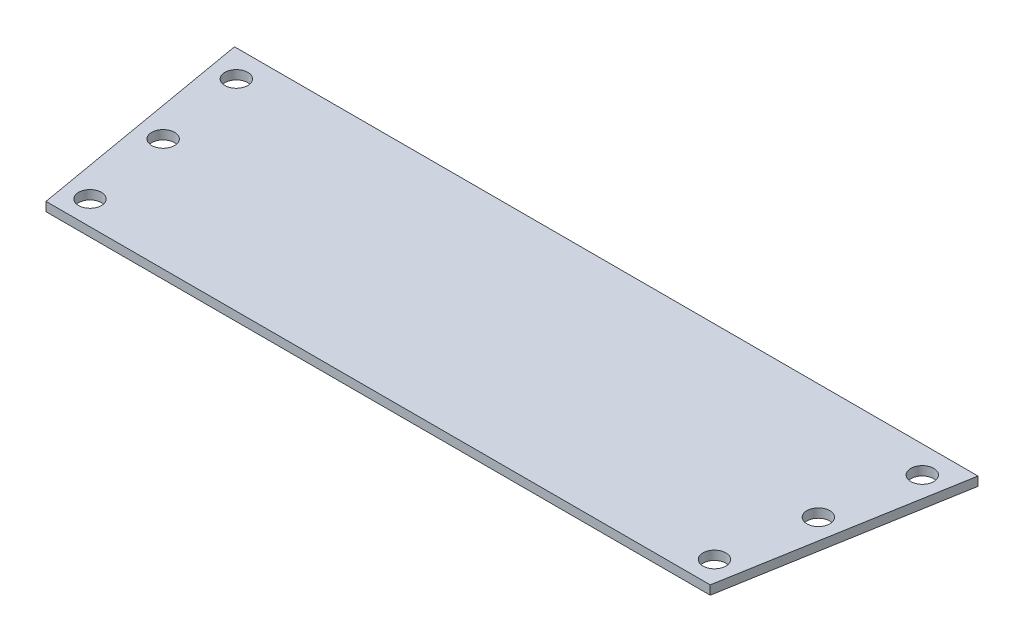
SolidWorks part; units mm, degrees
ref_plane "前视基准面" through (0, 0, 0) normal (0, 0, 1) x (1, 0, 0)
ref_plane "上视基准面" through (0, 0, 0) normal (0, 1, 0) x (1, 0, 0)
ref_plane "右视基准面" through (0, 0, 0) normal (1, 0, 0) x (0, 0, -1)
sketch "草图1" plane through (0, 0, 0) normal (0, 1, 0) x (1, 0, 0)
  line L14 (-100, 30) -> (100, 30)
  line L15 (-100, 30) -> (-100, -30)
  line L16 (-100, -30) -> (100, -30)
  line L17 (100, 30) -> (100, -30)
  line L18 (-100, 30) -> (100, -30) construction
  line L19 (-100, -30) -> (100, 30) construction
  point P0 (0, 0)
  dimension "D1" = 200
  dimension "D2" = 60
extrude "凸台-拉伸1" add sketch "草图1" along normal blind 2
sketch "草图3" plane through (0, 2, 0) normal (0, 1, 0) x (1, 0, 0)
  line L0 (-77.8265, -20.7713) -> (-86.6429, 30)
  line L2 (-77.8265, -20.7713) -> (82.1735, -20.7713)
  line L3 (82.1735, -20.7713) -> (90.9898, 30)
  line L4 (100, -30) -> (100, 30)
  line L5 (100, 30) -> (-100, 30)
  line L6 (-100, 30) -> (-100, -30)
  line L7 (-100, -30) -> (100, -30)
  line L8 (100, -30) -> (100, 30)
  line L9 (100, 30) -> (-100, 30)
  line L10 (-100, 30) -> (-100, -30)
  line L11 (-100, -30) -> (100, -30)
  circle A0 centre (-74.1534, 24) radius 2.55
  circle A1 centre (-70.7316, 4.2949) radius 2.55
  circle A2 centre (-67.3099, -15.4102) radius 2.55
  circle A3 centre (78.5003, 24) radius 2.55
  circle A4 centre (75.0785, 4.2949) radius 2.55
  circle A5 centre (71.6568, -15.4102) radius 2.55
  line M5 (100, -30) -> (100, 30)
  line M6 (100, 30) -> (-100, 30)
  line M7 (-100, 30) -> (-100, -30)
  line M8 (-100, -30) -> (100, -30)
  dimension "D2" = 5.1
  dimension "D1" = 0
extrude "切除-拉伸1" cut sketch "草图3" against normal through all contours L3 L2 L0 M6 M7 M8 M5 | A0 | A1 | A2 | A3 | A5 | A4
sketch "草图4" plane through (0, 0, 0) normal (0, -1, 0) x (1, 0, 0)
  line L0 (84.9, -30) -> (76.0837, 20.7713)
  line L1 (-80.5531, -30) -> (-71.7367, 20.7713)
  line L4 (90.9898, -30) -> (82.1735, 20.7713)
  line L5 (82.1735, 20.7713) -> (-77.8265, 20.7713)
  line L6 (-77.8265, 20.7713) -> (-86.6429, -30)
  line L7 (-86.6429, -30) -> (90.9898, -30)
  line L8 (90.9898, -30) -> (82.1735, 20.7713)
  line L9 (82.1735, 20.7713) -> (-77.8265, 20.7713)
  line L10 (-77.8265, 20.7713) -> (-86.6429, -30)
  line L11 (-86.6429, -30) -> (90.9898, -30)
  line M13 (90.9898, -30) -> (82.1735, 20.7713)
  line M14 (82.1735, 20.7713) -> (-77.8265, 20.7713)
  line M15 (-77.8265, 20.7713) -> (-86.6429, -30)
  line M16 (-86.6429, -30) -> (90.9898, -30)
  dimension "D2" = 6
  dimension "D3" = 6
  dimension "D1" = 0
extrude "切除-拉伸2" cut sketch "草图4" against normal through all contours L0 M16 M13 M14 | L1 M16 M14 M15
